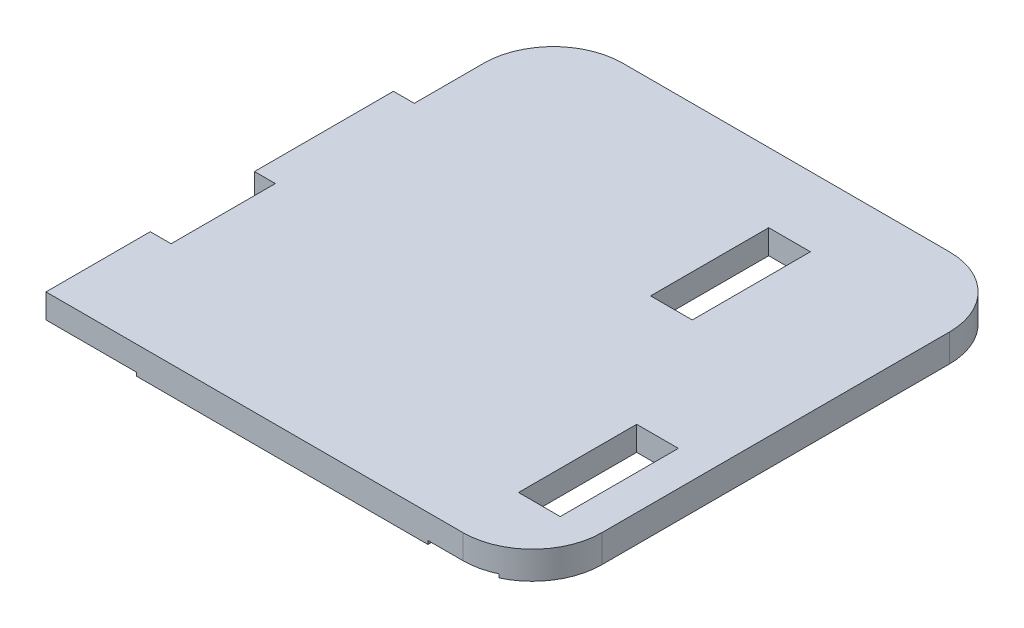
SolidWorks part; units mm, degrees
material "PBT General Purpose"
ref_plane "Front Plane" through (0, 0, 0) normal (0, 0, 1) x (1, 0, 0)
ref_plane "Top Plane" through (0, 0, 0) normal (0, 1, 0) x (1, 0, 0)
ref_plane "Right Plane" through (0, 0, 0) normal (1, 0, 0) x (0, 0, -1)
sketch "Sketch1" plane through (0, 0, 0) normal (0, 1, 0) x (1, 0, 0)
  line L0 (0, 0) -> (7, 0)
  line L5 (7, 0) -> (7, 7)
  line L6 (7, 7) -> (0.3, 7)
  line L7 (0.3, 7) -> (0.3, 5)
  line L8 (0.3, 5) -> (0, 5)
  line L9 (0, 5) -> (0, 3)
  line L10 (0, 3) -> (0.3, 3)
  line L11 (0.3, 3) -> (0.3, 1.5)
  line L12 (0.3, 1.5) -> (0, 1.5)
  line L13 (0, 1.5) -> (0, 0)
  line L15 (4.4, 6) -> (5, 6)
  line L16 (4.4, 6) -> (4.4, 4.3)
  line L17 (4.4, 4.3) -> (5, 4.3)
  line L18 (5, 6) -> (5, 4.3)
  line L19 (5.9, 0.9) -> (6.5, 0.9)
  line L20 (5.9, 0.9) -> (5.9, 2.6)
  line L21 (5.9, 2.6) -> (6.5, 2.6)
  line L22 (6.5, 0.9) -> (6.5, 2.6)
  dimension "D1" = 2
  dimension "D2" = 1.5
  dimension "D3" = 1.5
  dimension "D4" = 2
  dimension "D5" = 5.6
  dimension "D7" = 1.7
  dimension "D8" = 0.6
  dimension "D9" = 0.3
  dimension "D10" = 4.1
  dimension "D11" = 0.6
  dimension "D12" = 1.7
  dimension "D13" = 1
  dimension "D14" = 7
  dimension "D6" = 4.4
extrude "Boss-Extrude1" add sketch "Sketch1" along normal blind 0.4
fillet "Fillet1" radius 1 3 edges at (7, 0.2, 0) (7, 0.2, -7) (0.3, 0.2, -7)
sketch "Sketch2" plane through (0, 0, 0) normal (0, -1, 0) x (1, 0, 0)
  line L0 (5, -6) -> (4.8915, -6)
  line L1 (5, -6) -> (4.4, -6) construction
  line L2 (4.8915, -6) -> (4.8915, -7.2954)
  line L3 (4.8915, -7.2954) -> (4.0776, -7.2954)
  line L4 (4.0776, -7.2954) -> (4.0776, -4.1789)
  line L5 (4.3674, -3.7253) -> (5.2057, -3.3367)
  line L6 (5.4955, -2.8831) -> (5.4955, 0.5784)
  line L7 (5.4955, 0.5784) -> (6.4258, 0.5784)
  line L8 (6.4258, 0.5784) -> (6.4258, -0.9)
  line L9 (5.9, -0.9) -> (6.5, -0.9) construction
  line L10 (6.4258, -0.9) -> (6.5, -0.9)
  line L11 (6.5, -0.9) -> (6.5, -2.6)
  line L12 (6.5, -2.6) -> (6.4258, -2.6)
  line L13 (6.5, -2.6) -> (5.9, -2.6) construction
  line L14 (6.4258, -2.6) -> (6.4258, -3.3454)
  line L15 (6.1275, -3.8029) -> (5, -4.3)
  line L16 (5, -4.3) -> (5, -6)
  line L17 (1.3, -7) -> (1.3, 0)
  line L18 (0, 0) -> (6, 0) construction
  line L19 (1.3, 0) -> (-0.4281, 0)
  line L20 (-0.4281, 0) -> (-0.4281, -7)
  line L21 (-0.4281, -7) -> (1.3, -7)
  arc A0 (4.0776, -4.1789) -> (4.3674, -3.7253) centre (4.5776, -4.1789) cw
  arc A1 (5.4955, -2.8831) -> (5.2057, -3.3367) centre (4.9955, -2.8831) cw
  arc A2 (6.4258, -3.3454) -> (6.1275, -3.8029) centre (5.9258, -3.3454) cw
  dimension "D1" = 0.5
extrude "Cut-Extrude1" cut sketch "Sketch2" against normal blind 0.05
equation "\"t\"= 0.3'thickness of the sheets"
equation "\"FlexJoint\"= 0.15'Width of flextures"
equation "\"FoldJoint\"= 0.4'Width of folding joints"
equation "\"AssembleAngle\"= 90'Angle of assembly parts"
equation "\"D9@Sketch1\"=\"t\""
